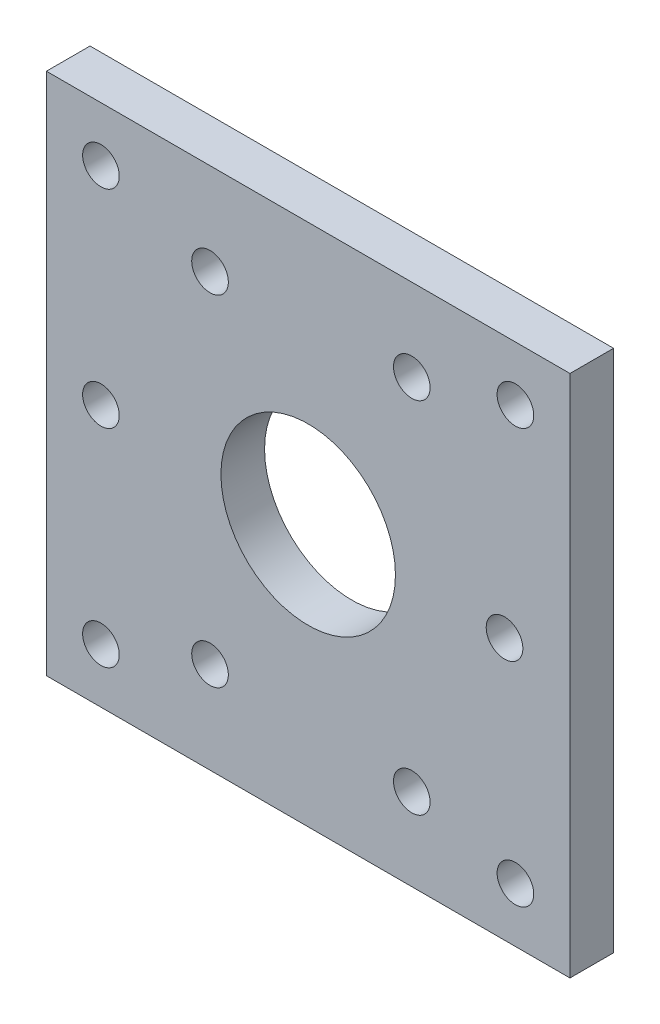
SolidWorks part; units mm, degrees
ref_plane "前视基准面" through (0, 0, 0) normal (0, 0, 1) x (1, 0, 0)
ref_plane "上视基准面" through (0, 0, 0) normal (0, 1, 0) x (1, 0, 0)
ref_plane "右视基准面" through (0, 0, 0) normal (1, 0, 0) x (0, 0, -1)
other "Configuration Table"
sketch "草图3" plane through (0, 0, 0) normal (0, 0, 1) x (1, 0, 0)
  line L1 (-30, -30) -> (30, -30)
  line L2 (-30, -30) -> (-30, 30)
  line L3 (-30, 30) -> (30, 30)
  line L4 (30, -30) -> (30, 30)
  line L5 (-30, -30) -> (30, 30) construction
  line L6 (-30, 30) -> (30, -30) construction
  circle A0 centre (0, 0) radius 10
  point P0 (0, 0)
  dimension "D3" = 20
  dimension "D1" = 60
  dimension "D2" = 60
extrude "凸台-拉伸2" add sketch "草图3" along normal blind 5
sketch "草图4" plane through (0, 0, 0) normal (0, 0, 1) x (1, 0, 0)
  line L0 (-1000, 0) -> (49000, 0) construction
  line L1 (0, -1000) -> (0, 49000) construction
  line L2 (0, 0) -> (25000, 43301.2702) construction
  line L3 (0, 0) -> (-25000, 43301.2702) construction
  line L5 (-23.75, -23.75) -> (23.75, -23.75) construction
  line L6 (-23.75, -23.75) -> (-23.75, 23.75) construction
  line L7 (-23.75, 23.75) -> (23.75, 23.75) construction
  line L8 (23.75, -23.75) -> (23.75, 23.75) construction
  line L9 (-23.75, -23.75) -> (23.75, 23.75) construction
  line L10 (-23.75, 23.75) -> (23.75, -23.75) construction
  circle A0 centre (0, 0) radius 22.5 construction
  circle A1 centre (0, 0) radius 23.75 construction
  circle A2 centre (11.875, 20.5681) radius 2.1
  circle A3 centre (22.5, 0) radius 2.1
  circle A4 centre (11.875, -20.5681) radius 2.1
  circle A5 centre (-11.25, -19.4856) radius 2.1
  circle A6 centre (-23.75, 0) radius 2.1
  circle A7 centre (-11.25, 19.4856) radius 2.1
  circle A8 centre (-23.75, 23.75) radius 2.1
  circle A9 centre (23.75, 23.75) radius 2.1
  circle A10 centre (23.75, -23.75) radius 2.1
  circle A11 centre (-23.75, -23.75) radius 2.1
  dimension "D3" = 45
  dimension "D4" = 47.5
  dimension "D5" = 4.2
  dimension "D6" = 4.2
  dimension "D7" = 4.2
  dimension "D8" = 4.2
  dimension "D9" = 4.2
  dimension "D10" = 4.2
  dimension "D13" = 4.2
  dimension "D14" = 4.2
  dimension "D15" = 4.2
  dimension "D16" = 4.2
  dimension "D1" = 30
  dimension "D2" = 30
  dimension "D11" = 47.5
  dimension "D12" = 47.5
extrude "切除-拉伸1" cut sketch "草图4" along normal up to surface (5 mm away) from surface at 0 up to face at (0, 0, 5) starting at face at (0, 0, 0)
